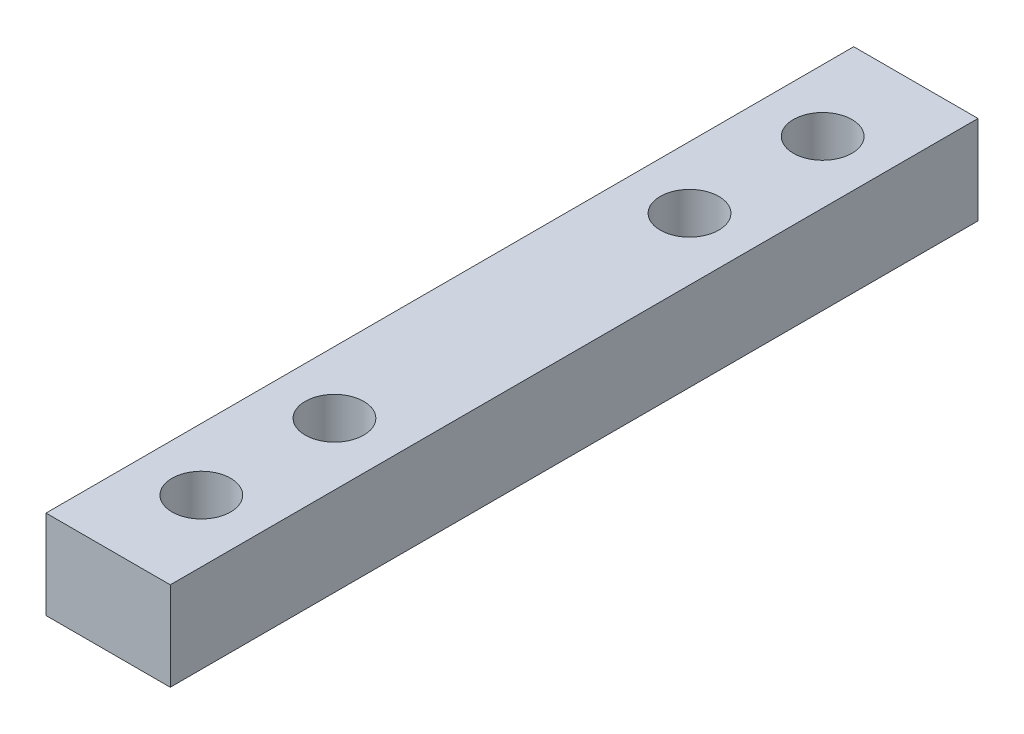
SolidWorks part; units mm, degrees
ref_plane "前视基准面" through (0, 0, 0) normal (0, 0, 1) x (1, 0, 0)
ref_plane "上视基准面" through (0, 0, 0) normal (0, 1, 0) x (1, 0, 0)
ref_plane "右视基准面" through (0, 0, 0) normal (1, 0, 0) x (0, 0, -1)
sketch "草图1" plane through (0, 0, 0) normal (0, 1, 0) x (1, 0, 0)
  line L1 (-3.5, 22.75) -> (3.5, 22.75)
  line L2 (-3.5, 22.75) -> (-3.5, -22.75)
  line L3 (-3.5, -22.75) -> (3.5, -22.75)
  line L4 (3.5, 22.75) -> (3.5, -22.75)
  line L5 (-3.5, 22.75) -> (3.5, -22.75) construction
  line L6 (-3.5, -22.75) -> (3.5, 22.75) construction
  point P0 (0, 0)
  dimension "D1" = 7
  dimension "D2" = 45.5
extrude "凸台-拉伸1" add sketch "草图1" along normal blind 5
sketch "草图2" plane through (0, 5, 0) normal (0, 1, 0) x (1, 0, 0)
  line L0 (0, 17.5) -> (0, -17.5) construction
  circle A0 centre (0, 17.5) radius 1.65
  circle A1 centre (0, -17.5) radius 1.65
  point P4 (0, 0)
  point P8 (0, -17.9839)
  dimension "D2" = 3.3
  dimension "D1" = 35
extrude "切除-拉伸1" cut sketch "草图2" against normal up to next
sketch "草图3" plane through (0, 5, 0) normal (0, 1, 0) x (1, 0, 0)
  line L0 (0, 10) -> (0, -10) construction
  circle A0 centre (0, 10) radius 1.65
  circle A1 centre (0, -10) radius 1.65
  point P4 (0, 0)
  dimension "D2" = 3.3
  dimension "D1" = 20
extrude "切除-拉伸2" cut sketch "草图3" against normal up to next
